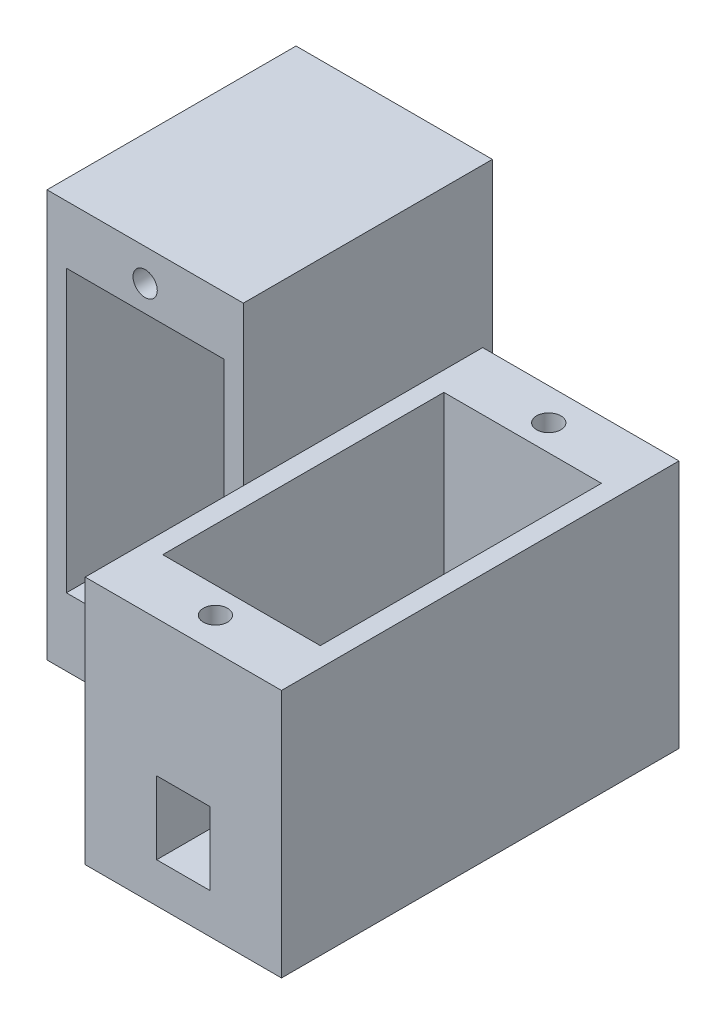
SolidWorks part; units mm, degrees
material "ABS"
ref_plane "Front Plane" through (0, 0, 0) normal (0, 0, 1) x (1, 0, 0)
ref_plane "Top Plane" through (0, 0, 0) normal (0, 1, 0) x (1, 0, 0)
ref_plane "Right Plane" through (0, 0, 0) normal (1, 0, 0) x (0, 0, -1)
sketch "Sketch1" plane through (0, 0, 0) normal (0, 1, 0) x (1, 0, 0)
  line L1 (-8.1, -10.9) -> (8.1, -10.9)
  line L2 (-8.1, -10.9) -> (-8.1, 21.9)
  line L3 (-8.1, 21.9) -> (8.1, 21.9)
  line L4 (8.1, -10.9) -> (8.1, 21.9)
extrude "Boss-Extrude1" add sketch "Sketch1" along normal mid plane 20.55 from offset 17.075
sketch "Sketch2" plane through (0, 0, 0) normal (0, 0, 1) x (1, 0, 0)
  line L1 (-24.3, 7.6) -> (-8.1, 7.6)
  line L2 (-24.3, 7.6) -> (-24.3, 40.4)
  line L3 (-24.3, 40.4) -> (-8.1, 40.4)
  line L4 (-8.1, 7.6) -> (-8.1, 40.4)
extrude "Boss-Extrude2" add sketch "Sketch2" along normal mid plane 20.55 from offset 12.425
sketch "Sketch3" plane through (0, 0, 0) normal (0, 1, 0) x (1, 0, 0)
  line L1 (-24.3, 2.15) -> (-8.1, 2.15)
  line L2 (-24.3, 2.15) -> (-24.3, 22.7)
  line L3 (-24.3, 22.7) -> (-8.1, 22.7)
  line L4 (-8.1, 2.15) -> (-8.1, 22.7)
extrude "Boss-Extrude3" add sketch "Sketch3" along normal mid plane 1 from offset 7.3
sketch "Sketch4" plane through (0, 0, 0) normal (0, 1, 0) x (1, 0, 0)
  line L1 (-6.5, -6.1) -> (6.5, -6.1)
  line L2 (-6.5, -6.1) -> (-6.5, 17.1)
  line L3 (-6.5, 17.1) -> (6.5, 17.1)
  line L4 (6.5, -6.1) -> (6.5, 17.1)
extrude "Cut-Extrude1" cut sketch "Sketch4" against normal mid plane 17.25 from offset 18.725
sketch "Sketch5" plane through (0, 0, 0) normal (0, 1, 0) x (1, 0, 0)
  circle A0 centre (0, 19.25) radius 1
extrude "Cut-Extrude2" cut sketch "Sketch5" against normal mid plane 6 from offset 24.35
sketch "Sketch6" plane through (0, 0, 0) normal (0, 1, 0) x (1, 0, 0)
  circle A0 centre (0, -8.25) radius 1
extrude "Cut-Extrude3" cut sketch "Sketch6" against normal mid plane 6 from offset 24.35
sketch "Sketch7" plane through (0, 0, 0) normal (0, 1, 0) x (1, 0, 0)
  circle A0 centre (0, 0) radius 3.15
extrude "Cut-Extrude4" cut sketch "Sketch7" against normal mid plane 2.6 from offset 8.1
sketch "Sketch8" plane through (0, 0, 0) normal (0, 0, 1) x (1, 0, 0)
  line L1 (-2.2, 10.1) -> (2.2, 10.1)
  line L2 (-2.2, 10.1) -> (-2.2, 16.1)
  line L3 (-2.2, 16.1) -> (2.2, 16.1)
  line L4 (2.2, 10.1) -> (2.2, 16.1)
extrude "Cut-Extrude5" cut sketch "Sketch8" against normal mid plane 4.8 from offset 8.5
sketch "Sketch9" plane through (0, 0, 0) normal (0, 0, 1) x (1, 0, 0)
  line L1 (-22.7, 12.4) -> (-9.7, 12.4)
  line L2 (-22.7, 12.4) -> (-22.7, 35.6)
  line L3 (-22.7, 35.6) -> (-9.7, 35.6)
  line L4 (-9.7, 12.4) -> (-9.7, 35.6)
extrude "Cut-Extrude6" cut sketch "Sketch9" against normal mid plane 17.25 from offset 10.775
sketch "Sketch10" plane through (0, 0, 0) normal (0, 0, 1) x (1, 0, 0)
  circle A0 centre (-16.2, 37.75) radius 1
extrude "Cut-Extrude7" cut sketch "Sketch10" against normal mid plane 6 from offset 5.15
sketch "Sketch11" plane through (0, 0, 0) normal (0, 0, 1) x (1, 0, 0)
  circle A0 centre (-16.2, 10.25) radius 1
extrude "Cut-Extrude8" cut sketch "Sketch11" against normal mid plane 6 from offset 5.15
sketch "Sketch12" plane through (0, 0, 0) normal (0, 0, 1) x (1, 0, 0)
  circle A0 centre (-16.2, 18.5) radius 3.15
extrude "Cut-Extrude9" cut sketch "Sketch12" against normal mid plane 2.6 from offset 21.4
sketch "Sketch13" plane through (0, 0, 0) normal (0, 1, 0) x (1, 0, 0)
  line L1 (-18.4, 13.4) -> (-14, 13.4)
  line L2 (-18.4, 13.4) -> (-18.4, 19.4)
  line L3 (-18.4, 19.4) -> (-14, 19.4)
  line L4 (-14, 13.4) -> (-14, 19.4)
extrude "Cut-Extrude10" cut sketch "Sketch13" against normal mid plane 4.8 from offset 10
